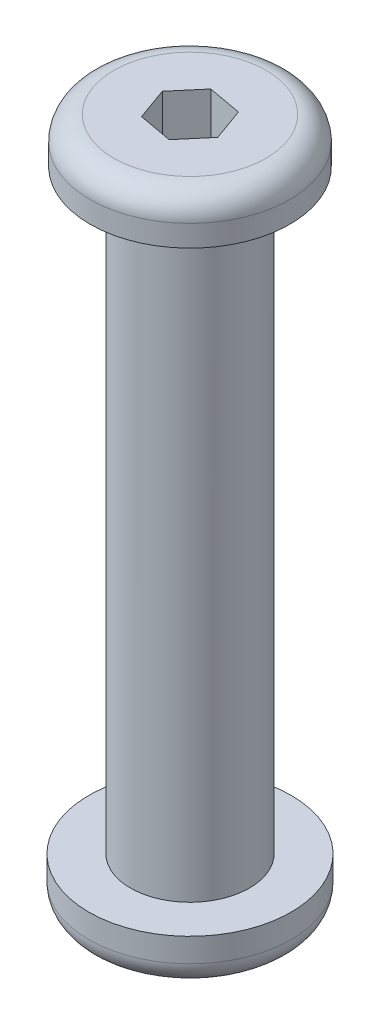
SolidWorks part; units mm, degrees
material "AISI 304"
ref_plane "前视基准面" through (0, 0, 0) normal (0, 0, 1) x (1, 0, 0)
ref_plane "上视基准面" through (0, 0, 0) normal (0, 1, 0) x (1, 0, 0)
ref_plane "右视基准面" through (0, 0, 0) normal (1, 0, 0) x (0, 0, -1)
other "Configuration Table"
sketch "草图1" plane through (0, 0, 0) normal (0, 1, 0) x (1, 0, 0)
  circle A0 centre (0, 0) radius 2.5
  dimension "D1" = 5
extrude "凸台-拉伸1" add sketch "草图1" along normal blind 25
sketch "草图2" plane through (0, 25, 0) normal (0, 1, 0) x (1, 0, 0)
  line L1 (0.9335, 1.1008) -> (-0.4866, 1.3589)
  line L2 (-0.4866, 1.3589) -> (-1.4201, 0.258)
  line L3 (-1.4201, 0.258) -> (-0.9335, -1.1008)
  line L4 (-0.9335, -1.1008) -> (0.4866, -1.3589)
  line L5 (0.4866, -1.3589) -> (1.4201, -0.258)
  line L6 (1.4201, -0.258) -> (0.9335, 1.1008)
  circle A0 centre (0, 0) radius 4.2
  circle A1 centre (0, 0) radius 1.25 construction
  dimension "D1" = 8.4
  dimension "D2" = 2.5
extrude "凸台-拉伸2" add sketch "草图2" along normal blind 1.9
sketch "草图3" plane through (0, 0, 0) normal (0, -1, 0) x (1, 0, 0)
  line L1 (0.8318, 1.1796) -> (-0.6057, 1.3102)
  line L2 (-0.6057, 1.3102) -> (-1.4375, 0.1305)
  line L3 (-1.4375, 0.1305) -> (-0.8318, -1.1796)
  line L4 (-0.8318, -1.1796) -> (0.6057, -1.3102)
  line L5 (0.6057, -1.3102) -> (1.4375, -0.1305)
  line L6 (1.4375, -0.1305) -> (0.8318, 1.1796)
  circle A0 centre (0, 0) radius 4.25
  circle A1 centre (0, 0) radius 1.25 construction
  dimension "D1" = 8.5
  dimension "D2" = 2.5
extrude "凸台-拉伸3" add sketch "草图3" along normal blind 2
fillet "圆角1" radius 1 2 edges at (0, 26.9, 4.2) (0, -2, -4.25)
